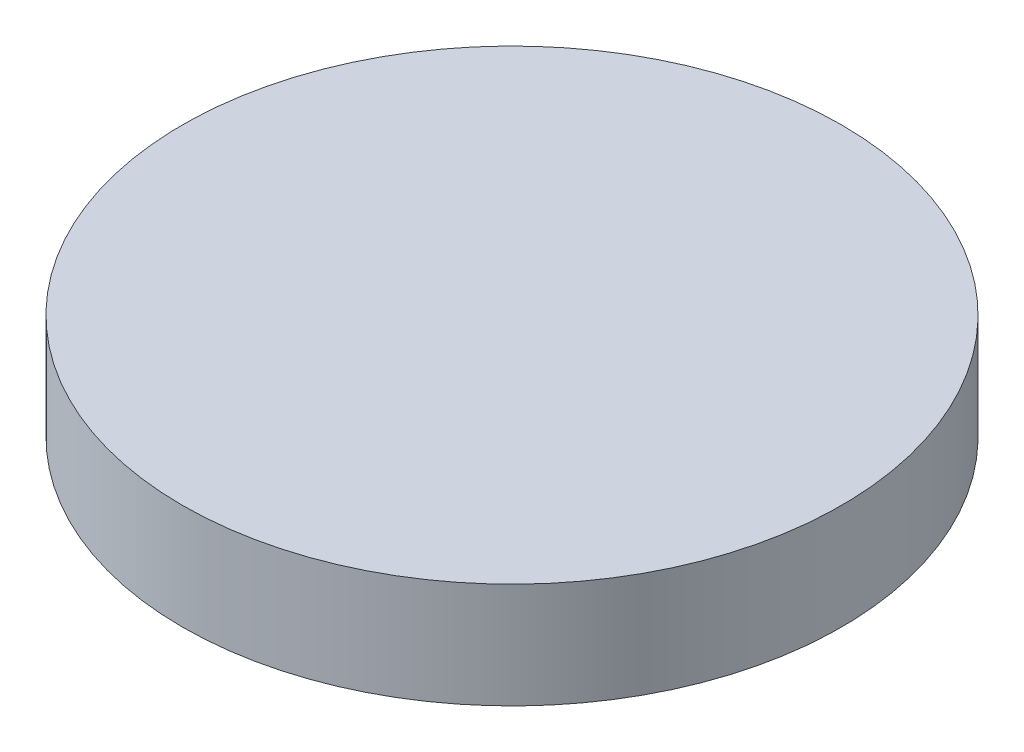
SolidWorks part; units mm, degrees
ref_plane "Front Plane" through (0, 0, 0) normal (0, 0, 1) x (1, 0, 0)
ref_plane "Top Plane" through (0, 0, 0) normal (0, 1, 0) x (1, 0, 0)
ref_plane "Right Plane" through (0, 0, 0) normal (1, 0, 0) x (0, 0, -1)
sketch "Sketch1" plane through (0, 0, 0) normal (0, 1, 0) x (1, 0, 0)
  circle A0 centre (0, 0) radius 12.5
  dimension "D1" = 25
extrude "Boss-Extrude1" add sketch "Sketch1" along normal blind 4
